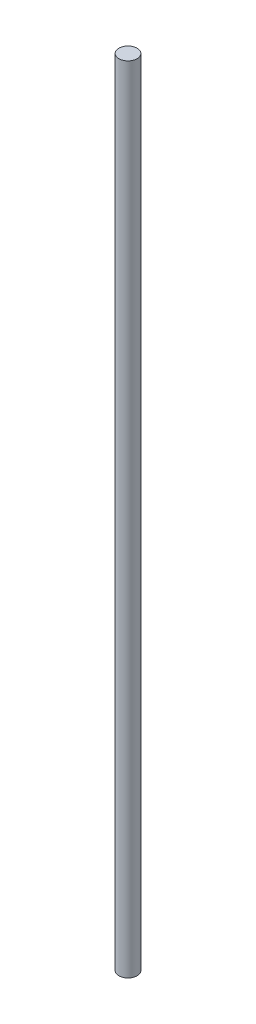
SolidWorks part; units mm, degrees
ref_plane "Alzado" through (0, 0, 0) normal (0, 0, 1) x (1, 0, 0)
ref_plane "Planta" through (0, 0, 0) normal (0, 1, 0) x (1, 0, 0)
ref_plane "Vista lateral" through (0, 0, 0) normal (1, 0, 0) x (0, 0, -1)
sketch "Croquis1" plane through (0, 0, 0) normal (0, 1, 0) x (1, 0, 0)
  circle A0 centre (0, 0) radius 6
  dimension "D1" = 12
extrude "Saliente-Extruir1" add sketch "Croquis1" along normal blind 523
